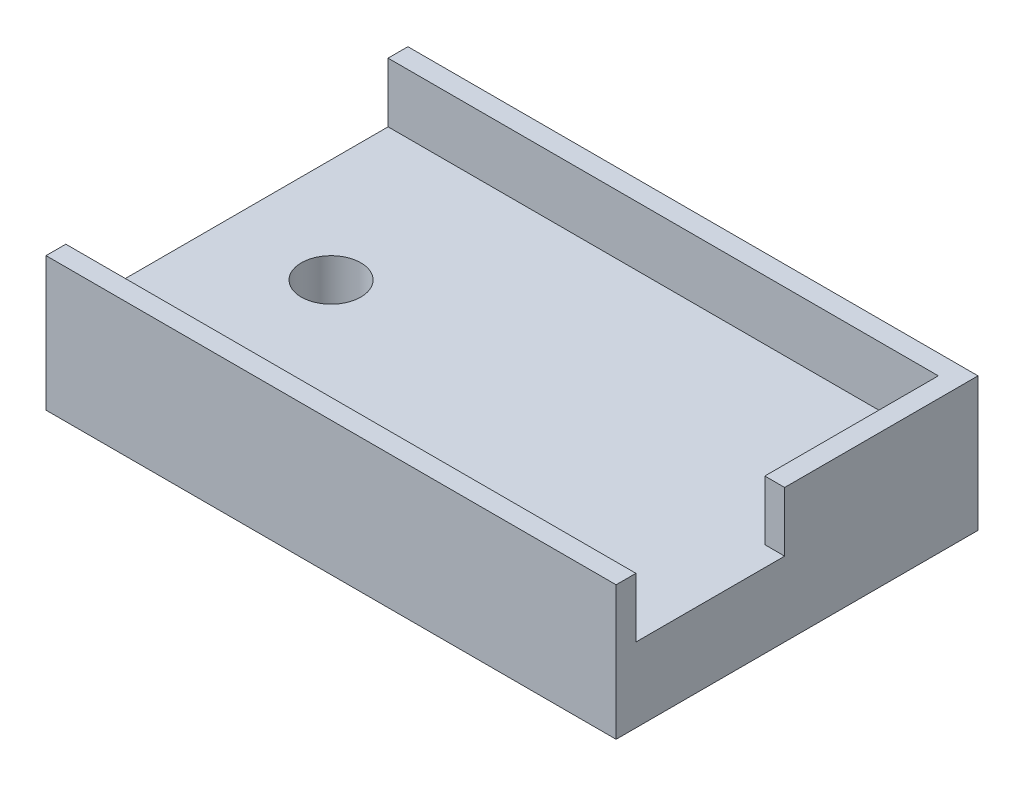
SolidWorks part; units mm, degrees
ref_plane "Front Plane" through (0, 0, 0) normal (0, 0, 1) x (1, 0, 0)
ref_plane "Top Plane" through (0, 0, 0) normal (0, 1, 0) x (1, 0, 0)
ref_plane "Right Plane" through (0, 0, 0) normal (1, 0, 0) x (0, 0, -1)
sketch "Sketch1" plane through (0, 0, 0) normal (0, 1, 0) x (1, 0, 0)
  line L1 (-11.5, 7.3) -> (11.5, 7.3)
  line L2 (-11.5, 7.3) -> (-11.5, -7.3)
  line L3 (-11.5, -7.3) -> (11.5, -7.3)
  line L4 (11.5, 7.3) -> (11.5, -7.3)
  line L5 (-11.5, 7.3) -> (11.5, -7.3) construction
  line L6 (-11.5, -7.3) -> (11.5, 7.3) construction
  point P0 (0, 0)
  dimension "D1" = 23
  dimension "D2" = 14.6
extrude "Boss-Extrude1" add sketch "Sketch1" along normal blind 3
sketch "Sketch2" plane through (0, 3, 0) normal (0, 1, 0) x (1, 0, 0)
  line L0 (11.5, -7.3) -> (11.5, 7.3) construction
  circle A0 centre (-7.3, 0) radius 1.2
  dimension "D2" = 2.4
  dimension "D1" = 18.8
extrude "Cut-Extrude1" cut sketch "Sketch2" against normal through all
sketch "Sketch3" plane through (0, 3, 0) normal (0, 1, 0) x (1, 0, 0)
  line L0 (-11.5, 7.3) -> (11.5, 7.3)
  line L1 (11.5, 7.3) -> (11.5, -0.5)
  line L2 (11.5, -7.3) -> (-11.5, -7.3)
  line L3 (-11.5, -7.3) -> (-11.5, -6.5)
  line L4 (-11.5, 7.3) -> (-11.5, -7.3) construction
  line L6 (10.7, -0.5) -> (10.7, 6.5)
  line L7 (10.7, 6.5) -> (-11.5, 6.5)
  line L8 (-11.5, 6.5) -> (-11.5, 7.3)
  line L10 (10.7, -0.5) -> (11.5, -0.5)
  line L11 (11.5, -6.5) -> (11.5, -7.3)
  line L12 (11.5, -6.5) -> (-11.5, -6.5)
  dimension "D1" = 0.8
  dimension "D2" = 0.8
  dimension "D3" = 0.8
  dimension "D4" = 6
extrude "Boss-Extrude2" add sketch "Sketch3" along normal blind 2.4
